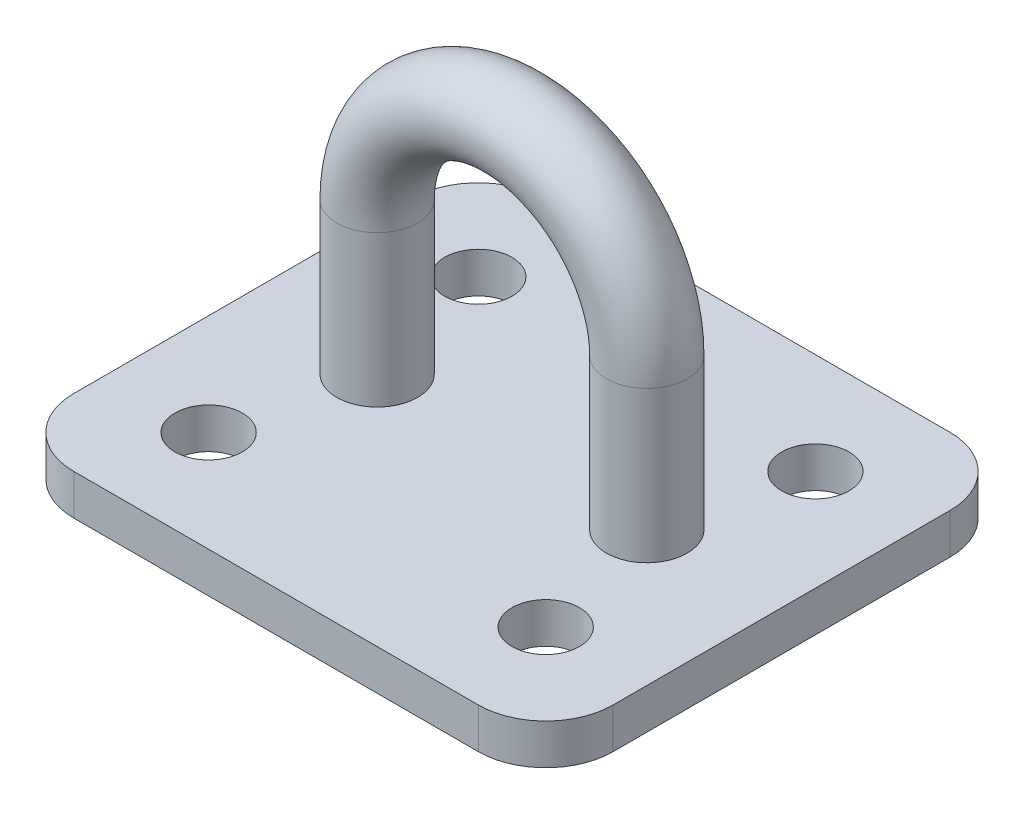
SolidWorks part; units mm, degrees
ref_plane "Front Plane" through (0, 0, 0) normal (0, 0, 1) x (1, 0, 0)
ref_plane "Top Plane" through (0, 0, 0) normal (0, 1, 0) x (1, 0, 0)
ref_plane "Right Plane" through (0, 0, 0) normal (1, 0, 0) x (0, 0, -1)
sketch "Sketch1" plane through (0, 0, 0) normal (0, 1, 0) x (1, 0, 0)
  line L0 (-15, 10) -> (15, 10) construction
  line L1 (15, -17.5) -> (-15, -17.5)
  line L2 (20, -12.5) -> (20, 12.5)
  line L3 (15, 17.5) -> (-15, 17.5)
  line L4 (-20, -12.5) -> (-20, 12.5)
  line L5 (20, -17.5) -> (-20, 17.5) construction
  line L6 (20, 17.5) -> (-20, -17.5) construction
  line L11 (0, 17.5) -> (0, -17.5) construction
  line L12 (-15, -10) -> (15, -10) construction
  arc A0 (-15, -17.5) -> (-20, -12.5) centre (-15, -12.5) cw
  arc A1 (15, -17.5) -> (20, -12.5) centre (15, -12.5) ccw
  arc A2 (20, 12.5) -> (15, 17.5) centre (15, 12.5) ccw
  arc A3 (-15, 17.5) -> (-20, 12.5) centre (-15, 12.5) ccw
  circle A4 centre (-12.5, 10) radius 2.5
  circle A5 centre (12.5, 10) radius 2.5
  circle A6 centre (-12.5, -10) radius 2.5
  circle A7 centre (12.5, -10) radius 2.5
  point P0 (0, 0)
  point P26 (0, 10)
  point P33 (0, -10)
  dimension "D3" = 5
  dimension "D4" = 5
  dimension "D5" = 30
  dimension "1" = 5
  dimension "D7" = 5
  dimension "D1" = 40
  dimension "D2" = 35
  dimension "D8" = 30
  dimension "D9" = 20
  dimension "D10" = 10
extrude "Boss-Extrude1" add sketch "Sketch1" along normal blind 3
sketch "Sketch2" plane through (0, 0, 0) normal (0, 1, 0) x (1, 0, 0)
  line L0 (-40.5254, 0) -> (50.0333, 0) construction
  circle A0 centre (-10, 0) radius 3
  dimension "D1" = 6
  dimension "D2" = 10
sketch "Sketch3" plane through (0, 0, 0) normal (0, 0, 1) x (1, 0, 0)
  line L0 (-10, 0) -> (-10, 14.2)
  line L1 (-10, 14.2) -> (10, 14.2) construction
  line L4 (10, 14.2) -> (10, 0)
  line L5 (-40.5254, 0) -> (50.0333, 0) construction
  line L6 (-15, 3) -> (15, 3) construction
  arc A0 (10, 14.2) -> (-10, 14.2) centre (0, 14.2) ccw
  dimension "D1" = 11.2
  dimension "D2" = 20
sweep "Sweep1" add profiles "Sketch2" path "Sketch3"
